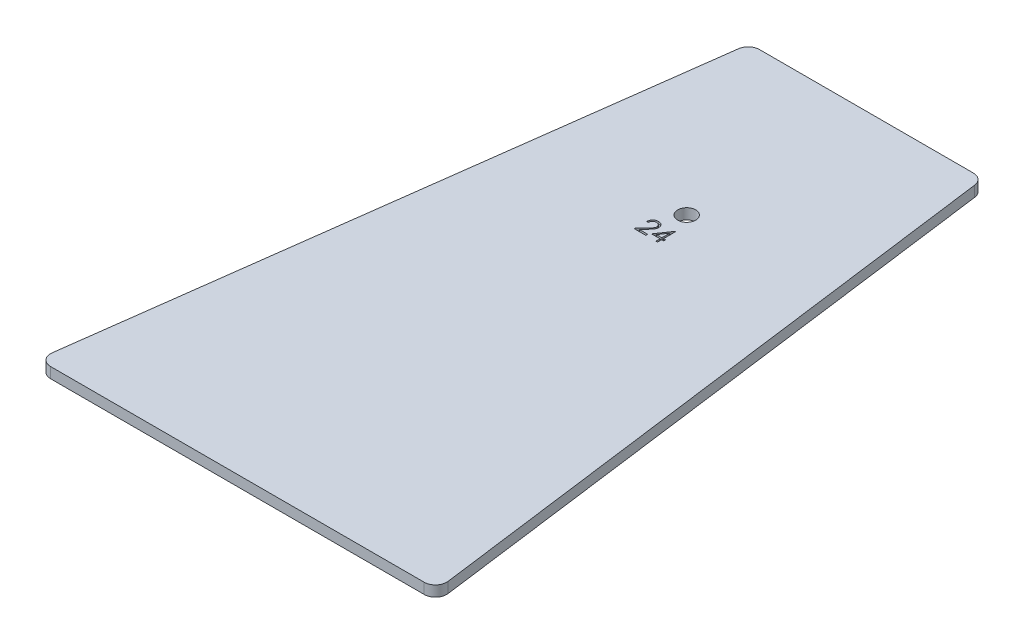
SolidWorks part; units mm, degrees
material "Acrylic (Medium-high impact)"
ref_plane "Front Plane" through (0, 0, 0) normal (0, 0, 1) x (1, 0, 0)
ref_plane "Top Plane" through (0, 0, 0) normal (0, 1, 0) x (1, 0, 0)
ref_plane "Right Plane" through (0, 0, 0) normal (1, 0, 0) x (0, 0, -1)
sketch "Sketch1" plane through (0, 0, 0) normal (0, 1, 0) x (1, 0, 0)
  line L0 (0, 0) -> (0, -355.6) construction
  line L1 (-66.04, 0) -> (66.04, 0)
  line L2 (66.04, 0) -> (112.8556, -355.6)
  line L3 (112.8556, -355.6) -> (-112.8556, -355.6)
  line L4 (-66.04, 0) -> (-112.8556, -355.6)
  dimension "D1" = 355.6
  dimension "D2" = 15
  dimension "D3" = 132.08
extrude "Boss-Extrude1" add sketch "Sketch1" along normal blind 5.9944
sketch "Sketch2" plane through (0, 5.9944, 0) normal (0, 1, 0) x (1, 0, 0)
  line L0 (0, 0) -> (0, -101.6) construction
  line L1 (66.04, 0) -> (-66.04, 0) construction
  circle A0 centre (0, -101.6) radius 5.08
  dimension "D2" = 10.16
  dimension "D1" = 101.6
extrude "Cut-Extrude1" cut sketch "Sketch2" against normal through all
sketch "Sketch3" plane through (0, 5.9944, 0) normal (0, 1, 0) x (1, 0, 0)
  line L2 (0, -101.6) -> (0, -112.5534) construction
  line L3 (-8.9196, -123.1153) -> (7.5904, -123.1153) construction
  line L4 (-8.9196, -123.1153) -> (-8.9196, -112.9553) construction
  line L5 (-8.9196, -112.9553) -> (7.5904, -112.9553) construction
  line L6 (7.5904, -123.1153) -> (7.5904, -112.9553) construction
  text T0 "24" font "Century Gothic" height 10.16
  point P1 (-3.1646, -119.3765)
  dimension "D1" = 10.16
  dimension "D2" = 16.51
extrude "Cut-Extrude2" cut sketch "Sketch3" against normal blind 1.27
fillet "Fillet1" radius 6.35 4 edges at (112.8556, 2.9972, 355.6) (-112.8556, 2.9972, 355.6) (-66.04, 2.9972, 0) (66.04, 2.9972, 0)
